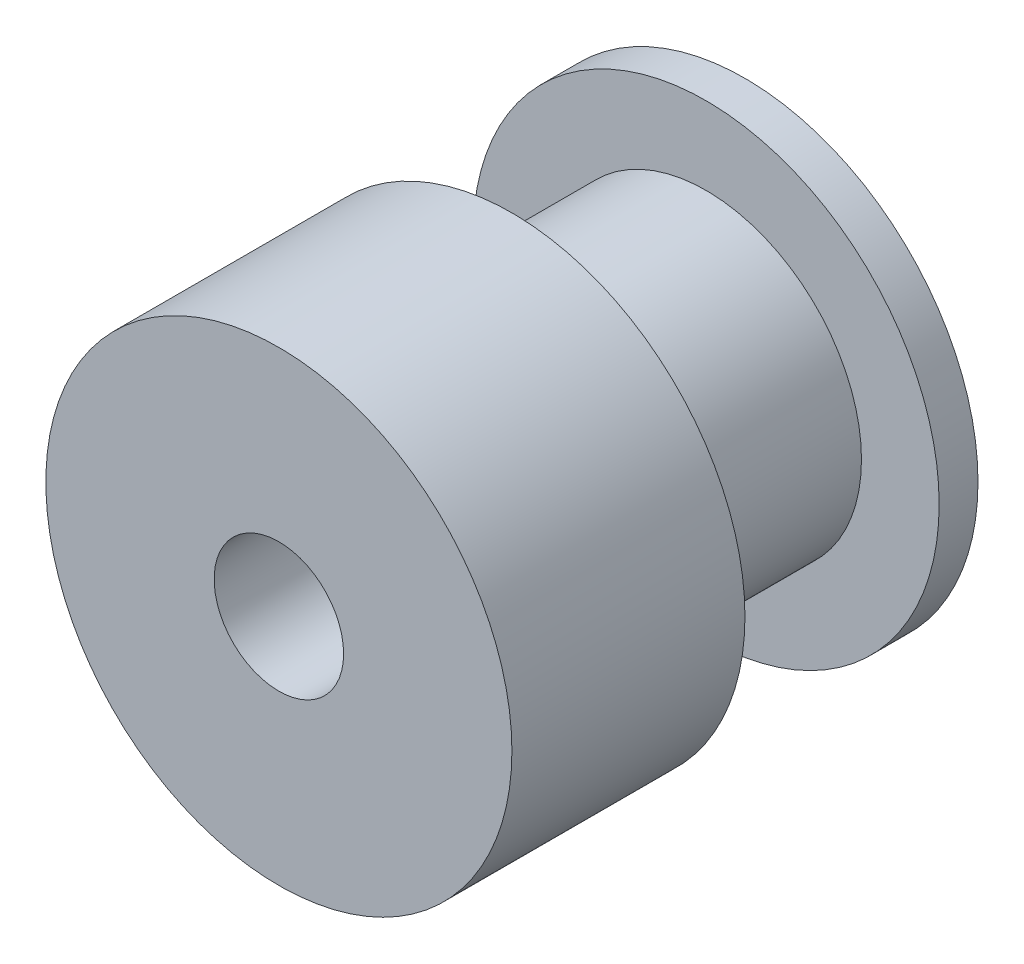
SolidWorks part; units mm, degrees
ref_plane "Plan de face" through (0, 0, 0) normal (0, 0, 1) x (1, 0, 0)
ref_plane "Plan de dessus" through (0, 0, 0) normal (0, 1, 0) x (1, 0, 0)
ref_plane "Plan de droite" through (0, 0, 0) normal (1, 0, 0) x (0, 0, -1)
sketch "Esquisse1" plane through (0, 0, 0) normal (0, 0, 1) x (1, 0, 0)
  circle A0 centre (0, 0) radius 9
  dimension "D1" = 18
extrude "Boss.-Extru.1" add sketch "Esquisse1" along normal blind 18
sketch "Esquisse2" plane through (0, 0, 0) normal (0, 0, 1) x (1, 0, 0)
  circle A0 centre (0, 0) radius 6
  circle A1 centre (0, 0) radius 9
  dimension "D1" = 12
extrude "Enlèv. mat.-Extru.1" cut sketch "Esquisse2" along normal blind 7.5 from offset 1.5
sketch "Esquisse3" plane through (0, 0, 0) normal (0, 0, 1) x (1, 0, 0)
  circle A0 centre (0, 0) radius 2.5
  dimension "D1" = 5
extrude "Enlèv. mat.-Extru.3" cut sketch "Esquisse3" along normal through all contours A0
sketch "Esquisse4" plane through (0, 0, 0) normal (0, 1, 0) x (1, 0, 0)
  line L0 (0, -13.5) -> (0, -9) construction
  line L1 (9, -9) -> (-9, -9) construction
  line L2 (0, -13.5) -> (0, -18) construction
  line L3 (-9, -18) -> (9, -18) construction
  circle A0 centre (0, -13.5) radius 1.25
  dimension "D1" = 2.5
extrude "Enlèv. mat.-Extru.4" cut sketch "Esquisse4" against normal through all
pattern_circular "Répétition circulaire1" count 2 over 90 about axis through (0, 0, 18) along (0, 0, -1) of "Enlèv. mat.-Extru.4"
